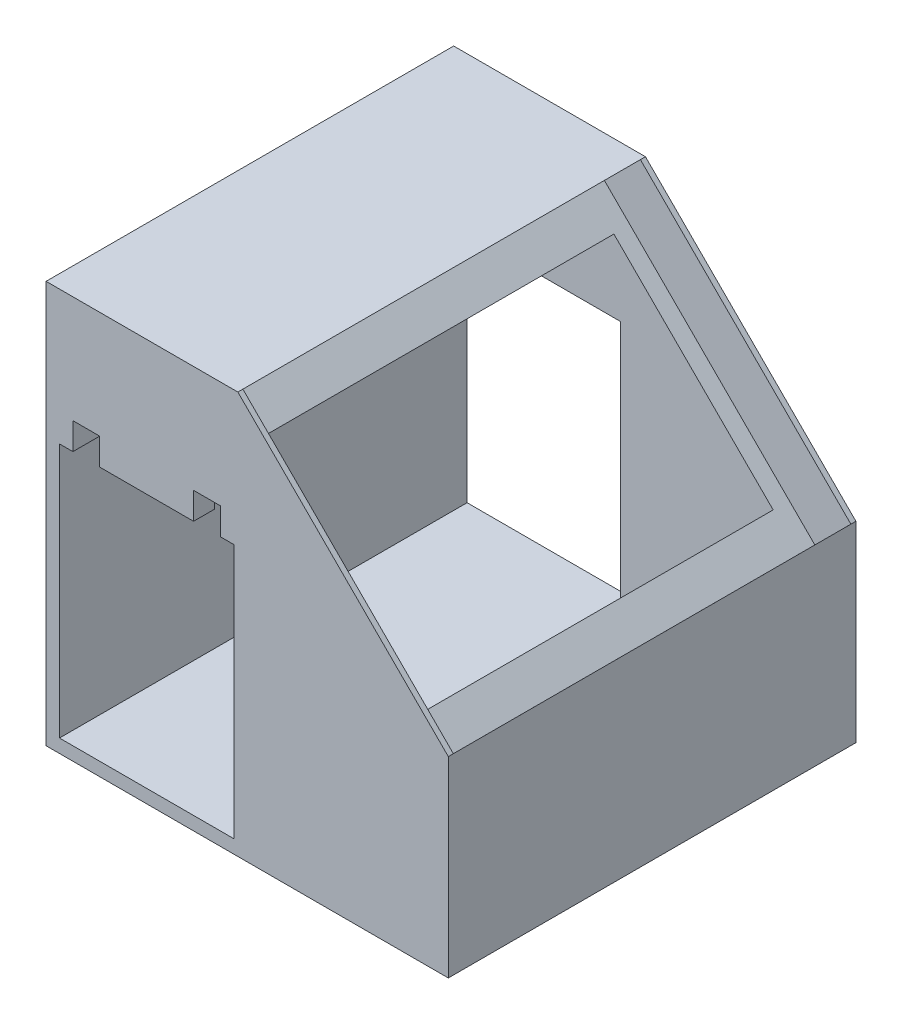
SolidWorks part; units mm, degrees
ref_plane "Front Plane" through (0, 0, 0) normal (0, 0, 1) x (1, 0, 0)
ref_plane "Top Plane" through (0, 0, 0) normal (0, 1, 0) x (1, 0, 0)
ref_plane "Right Plane" through (0, 0, 0) normal (1, 0, 0) x (0, 0, -1)
sketch "Sketch1" plane through (0, 0, 0) normal (0, 0, 1) x (1, 0, 0)
  line L1 (0, 0) -> (150, 0)
  line L2 (0, 0) -> (0, 150)
  line L3 (0, 150) -> (150, 150)
  line L4 (150, 0) -> (150, 150)
  line L5 (5, 5) -> (70, 5)
  line L6 (5, 5) -> (5, 100)
  line L7 (5, 100) -> (70, 100)
  line L8 (70, 5) -> (70, 100)
  dimension "D1" = 150
  dimension "D2" = 150
  dimension "D3" = 65
  dimension "D4" = 95
  dimension "D5" = 5
  dimension "D6" = 5
extrude "Boss-Extrude2" add sketch "Sketch1" along normal blind 152 contours L8 L7 L6 L5 | L3 L4 L1 L2
chamfer "Chamfer1" distance 78.4889 angle 45 1 edges at (150, 150, 76)
sketch "Sketch4" plane through (110.7556, 110.7556, 0) normal (0.7071, 0.7071, 0) x (0, 0, -1)
  line L0 (-152, -55.5) -> (-152, 55.5) construction
  line L1 (-150.125, 55.5019) -> (-1.875, 55.5019)
  line L2 (-150.125, 55.5019) -> (-150.125, -55.4981)
  line L3 (-150.125, -55.4981) -> (-1.875, -55.4981)
  line L4 (-1.875, 55.5019) -> (-1.875, -55.4981)
  dimension "D1" = 148.25
  dimension "D2" = 111
  dimension "D3" = 1.875
extrude "Cut-Extrude5" cut sketch "Sketch4" against normal blind 19
sketch "Sketch5" plane through (97.3205, 97.3205, 0) normal (0.7071, 0.7071, 0) x (0, 0, -1)
  line L0 (-150.125, -55.4981) -> (-1.875, -55.4981) construction
  line L1 (-144.125, 42.0019) -> (-7.875, 42.0019)
  line L2 (-144.125, 42.0019) -> (-144.125, -41.9981)
  line L3 (-144.125, -41.9981) -> (-7.875, -41.9981)
  line L4 (-7.875, 42.0019) -> (-7.875, -41.9981)
  line L5 (-1.875, -55.4981) -> (-1.875, 55.5) construction
  line L6 (-150.125, 55.5019) -> (-150.125, -55.4981) construction
  line L7 (-1.875, 55.5019) -> (-150.125, 55.5019) construction
  dimension "D1" = 13.5
  dimension "D2" = 6
  dimension "D3" = 6
  dimension "D4" = 13.5
extrude "Cut-Extrude6" cut sketch "Sketch5" against normal blind 81
sketch "Sketch6" plane through (0, 0, 152) normal (0, 0, 1) x (1, 0, 0)
  line L0 (5, 5) -> (5, 100) construction
  line L1 (10, 110) -> (20, 110)
  line L2 (10, 110) -> (10, 100)
  line L3 (10, 100) -> (20, 100)
  line L4 (20, 110) -> (20, 100)
  line L5 (5, 100) -> (70, 100) construction
  dimension "D1" = 10
  dimension "D2" = 10
  dimension "D3" = 15
  dimension "D4" = 0
extrude "Cut-Extrude7" cut sketch "Sketch6" against normal blind 40
sketch "Sketch7" plane through (0, 0, 152) normal (0, 0, 1) x (1, 0, 0)
  line L0 (70, 5) -> (70, 100) construction
  line L1 (55, 110) -> (65, 110)
  line L2 (55, 110) -> (55, 100)
  line L3 (55, 100) -> (65, 100)
  line L4 (65, 110) -> (65, 100)
  line L5 (20, 100) -> (70, 100) construction
  dimension "D1" = 10
  dimension "D2" = 10
  dimension "D3" = 15
  dimension "D4" = 0
extrude "Cut-Extrude8" cut sketch "Sketch7" against normal blind 40
sketch "Sketch10" plane through (0, 100, 0) normal (0, -1, 0) x (1, 0, 0)
  line L1 (20, 112) -> (60, 112)
  line L2 (20, 112) -> (20, 118)
  line L3 (20, 118) -> (60, 118)
  line L4 (60, 112) -> (60, 118)
  dimension "D1" = 6
  dimension "D2" = 40
extrude "Cut-Extrude10" cut sketch "Sketch10" against normal blind 10
